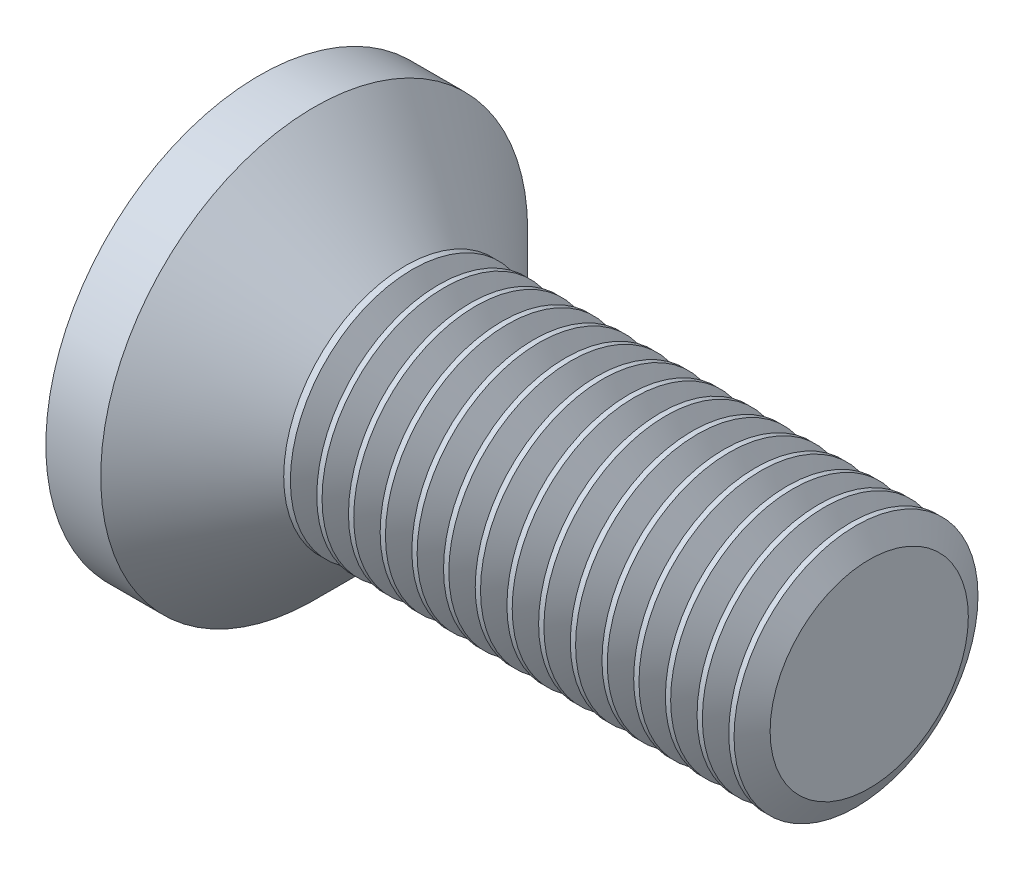
SolidWorks part; units mm, degrees
ref_plane "Front" through (0, 0, 0) normal (0, 0, 1) x (1, 0, 0)
ref_plane "Top" through (0, 0, 0) normal (0, 1, 0) x (1, 0, 0)
ref_plane "Right" through (0, 0, 0) normal (1, 0, 0) x (0, 0, -1)
other "Configuration Table"
sketch "Sketch1" plane through (0, 0, 0) normal (0, 0, 1) x (1, 0, 0)
  line L0 (5, 1) -> (2, 1)
  line L1 (2, 1) -> (1.2, 1)
  line L2 (1.2, 1) -> (0.45, 1.75)
  line L3 (0.45, 1.75) -> (0, 1.75)
  line L4 (5, 1) -> (5, 0)
  line L5 (4.5158, 0) -> (-89.8219, 0) construction
  line L6 (5, 0) -> (0, 0)
  line L7 (0, 1.75) -> (0, 0)
  dimension "d" = 2
  dimension "D1" = 45
  dimension "dk" = 3.5
  dimension "k" = 1.2
  dimension "l" = 5
  dimension "a" = 0.8
revolve "Base" add sketch "Sketch1" angle 360 about L5
cosmetic thread "ThreadCosmetic1" [suppressed] parameters "bb"=3.8, "THD_MINOR"=1.567
sketch "Sketch6" plane through (0, 0, 0) normal (1, 0, 0) x (0, 0, -1)
  line L0 (-1.9271, 0) -> (2.0512, 0) construction
  line L1 (0, 1.8651) -> (0, -2.0207) construction
  line L2 (0.19, 0.19) -> (0.19, 0.95)
  line L3 (0.19, 0.95) -> (-0.19, 0.95)
  line L4 (-0.19, 0.19) -> (-0.19, 0.95)
  line L5 (0.19, 0.19) -> (0.95, 0.19)
  line L6 (0.95, 0.19) -> (0.95, -0.19)
  line L7 (-0.95, 0.19) -> (-0.95, -0.19)
  line L8 (-0.19, 0.19) -> (-0.95, 0.19)
  line L9 (-0.19, -0.19) -> (-0.95, -0.19)
  line L10 (0.19, -0.19) -> (0.95, -0.19)
  line L11 (-0.19, -0.19) -> (-0.19, -0.95)
  line L12 (0.19, -0.95) -> (-0.19, -0.95)
  line L13 (0.19, -0.19) -> (0.19, -0.95)
  point P16 (-0.95, 0)
  point P17 (0.95, 0)
extrude "CrossRecess" cut sketch "Sketch6" along normal blind 0.6
draft "Draft9" type of draft neutral plane draft angle 30 faces to draft 4 face at (0.3, 0.95, 0) face at (0.3, 0, 0.95) face at (0.3, -0.95, 0) face at (0.3, 0, -0.95) neutral plane through (0, 1.75, 0) neutral plane normal (-1, 0, 0) parameters "D1"=30
fillet "Fillet5" radius 0.3 4 edges at (0.3, -0.19, -0.19) (0.3, 0.19, -0.19) (0.3, 0.19, 0.19) (0.3, -0.19, 0.19)
sketch "Sketch7" plane through (0, 0, 0) normal (1, 0, 0) x (0, 0, -1)
  line L0 (-2.0126, 0) -> (1.9757, 0) construction
  line L1 (0, 1.9314) -> (0, -2.0126) construction
  line L2 (0, 0) -> (1.5555, 1.5555) construction
  line L3 (0, 0.2839) -> (0.6718, 0.6718)
  line L4 (-1.5402, 1.5402) -> (0, 0) construction
  line L5 (0.2839, 0) -> (0.6718, 0.6718)
  line L6 (0, -0.2839) -> (0.6718, -0.6718)
  line L7 (0.2839, 0) -> (0.6718, -0.6718)
  line L8 (-0.2839, 0) -> (-0.6718, -0.6718)
  line L9 (0, -0.2839) -> (-0.6718, -0.6718)
  line L10 (-0.2839, 0) -> (-0.6718, 0.6718)
  line L11 (0, 0.2839) -> (-0.6718, 0.6718)
  dimension "D3" = 15
  dimension "m" = 1.9
extrude "Cut-Extrude3" [suppressed] cut sketch "Sketch7" along normal blind 10 draft 20
sketch "Sketch8" plane through (0, 0, 0) normal (0, 0, 1) x (1, 0, 0)
  line L0 (-20, 1.2165) -> (-21, 1)
  line L1 (-21, 1) -> (1.2, 1)
  line L3 (5, -1) -> (5, 1) construction
  line L6 (1.2, 1) -> (1.2, 6)
  line L7 (1.2, 6) -> (-20, 6)
  line L8 (-20, 6) -> (-20, 1.2165)
  line L9 (62.4753, 0.2165) -> (52.9594, 0.2165) construction
  dimension "D1" = 5
  dimension "x" = 1
  dimension "d" = 2
  dimension "THD_MINOR" = 1.567
  dimension "b" = 25
sketch "Sketch9" plane through (0, 0, 0) normal (0, 0, 1) x (1, 0, 0)
  line L0 (5, 0.8125) -> (5.1082, 1)
  line L1 (5.1082, 1) -> (5.1082, 1.2165)
  line L2 (5.1082, 1.2165) -> (4.8918, 1.2165)
  line L3 (4.8918, 1.2165) -> (4.8918, 1)
  line L4 (4.8918, 1) -> (5, 0.8125)
  line L5 (0, 0) -> (73.843, 0) construction
  line L6 (5, -1) -> (5, 1) construction
  dimension "D1" = 2
  dimension "D2" = 0.2165
revolve "Cut-Revolve10" cut sketch "Sketch9" angle 360 about L5
pattern_linear "LPattern10" count 15 spacing 0.2598 along (-1, 0, 0) of "Cut-Revolve10"
equation "\"D1@Sketch6\" = \"m@Sketch6\" / 5"
equation "\"D1@CrossRecess\" = \"k@Sketch1\" / 2"
equation "\"D1@Sketch9\" = \"d@Sketch1\""
equation "\"D2@Sketch9\" =  ( \"d@Sketch1\" - \"THD_MINOR@ThreadCosmetic1\" )  / 2"
equation "\"D3@LPattern10\" = \"D2@Sketch9\" * 1.2"
equation "\"D1@LPattern10\" = \"bb@ThreadCosmetic1\" / \"D3@LPattern10\" "
